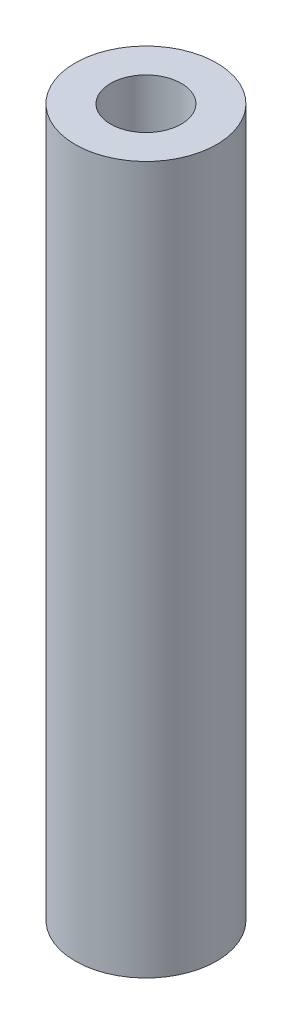
SolidWorks part; units mm, degrees
material "6061 合金"
ref_plane "前视基准面" through (0, 0, 0) normal (0, 0, 1) x (1, 0, 0)
ref_plane "上视基准面" through (0, 0, 0) normal (0, 1, 0) x (1, 0, 0)
ref_plane "右视基准面" through (0, 0, 0) normal (1, 0, 0) x (0, 0, -1)
sketch "草图1" plane through (0, 0, 0) normal (0, 1, 0) x (1, 0, 0)
  circle A0 centre (0, 0) radius 1
  circle A1 centre (0, 0) radius 2
  dimension "D1" = 2
  dimension "D2" = 4
extrude "凸台-拉伸1" add sketch "草图1" along normal blind 20
